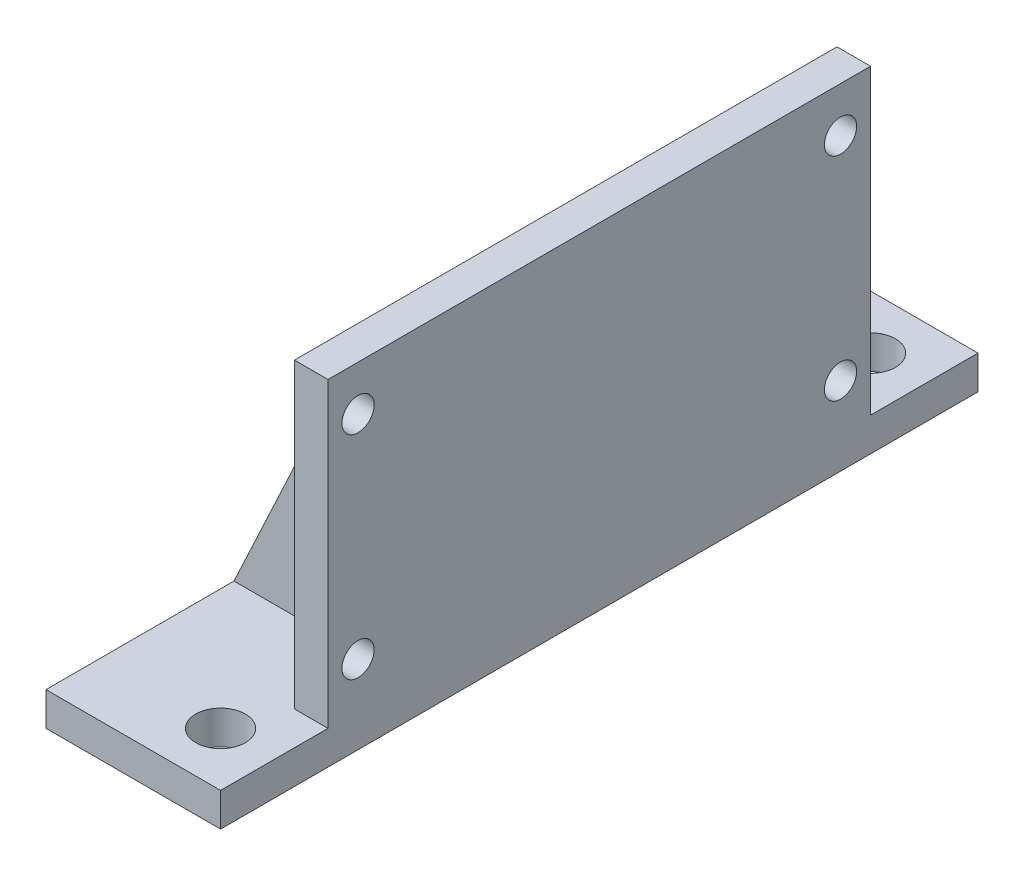
SolidWorks part; units mm, degrees
ref_plane "Front Plane" through (0, 0, 0) normal (0, 0, 1) x (1, 0, 0)
ref_plane "Top Plane" through (0, 0, 0) normal (0, 1, 0) x (1, 0, 0)
ref_plane "Right Plane" through (0, 0, 0) normal (1, 0, 0) x (0, 0, -1)
sketch "Sketch1" plane through (0, 0, 0) normal (0, 1, 0) x (1, 0, 0)
  line L0 (0, 0) -> (0, 61.4723)
  line L2 (0, 0) -> (-5.08, 0)
  line L3 (0, 0) -> (0, 5.08)
  line L4 (0, 5.08) -> (-5.08, 5.08)
  line L5 (-5.08, 0) -> (-5.08, 5.08)
  line L6 (-5.08, 5.08) -> (5.08, 5.08)
  line L7 (-5.08, 5.08) -> (-5.08, -5.08)
  line L8 (-5.08, -5.08) -> (5.08, -5.08)
  line L9 (5.08, 5.08) -> (5.08, -5.08)
  line L10 (0, 61.4723) -> (5.08, 61.4723)
  line L11 (0, 61.4723) -> (0, 56.3923)
  line L12 (0, 56.3923) -> (5.08, 56.3923)
  line L13 (5.08, 61.4723) -> (5.08, 56.3923)
  line L14 (5.08, 56.3923) -> (-5.08, 56.3923)
  line L15 (5.08, 56.3923) -> (5.08, 66.5523)
  line L16 (5.08, 66.5523) -> (-5.08, 66.5523)
  line L17 (-5.08, 56.3923) -> (-5.08, 66.5523)
  line L18 (-5.08, 56.3923) -> (5.08, 56.3923)
  line L19 (-5.08, 56.3923) -> (-5.08, 5.08)
  line L20 (-5.08, 5.08) -> (5.08, 5.08)
  line L21 (5.08, 56.3923) -> (5.08, 5.08)
  line L22 (-5.08, 66.5523) -> (-11.43, 66.5523)
  line L23 (-5.08, 66.5523) -> (-5.08, -5.08)
  line L24 (-5.08, -5.08) -> (-11.43, -5.08)
  line L25 (-11.43, 66.5523) -> (-11.43, -5.08)
  circle A1 centre (0, 61.4723) radius 2.3495
  circle A2 centre (0, 0) radius 2.3495
  dimension "D2" = 4.699
  dimension "D3" = 4.699
  dimension "D1" = 61.4723
  dimension "D4" = 5.08
  dimension "D5" = 10.16
  dimension "D6" = 5.08
  dimension "D7" = 10.16
  dimension "D8" = 6.35
extrude "Boss-Extrude1" add sketch "Sketch1" along normal blind 3.175 contours A1 L10 L15 L16 L17 L14 L0 | A1 L0 L12 L13 L10 | L14 L19 L4 L0 | L21 L12 L0 L6 | A2 L3 L4 L5 L2 | A2 L2 L7 L8 L9 L6 L3 | L22 L25 L24 L7 L5 L19 L17
sketch "Sketch2" plane through (5.08, 0, 0) normal (1, 0, 0) x (0, 0, -1)
  line L1 (5.08, 3.175) -> (56.3923, 3.175)
  line L2 (5.08, 3.175) -> (5.08, 31.75)
  line L3 (5.08, 31.75) -> (56.3923, 31.75)
  line L4 (56.3923, 3.175) -> (56.3923, 31.75)
  line L5 (66.5523, 3.175) -> (66.5523, 0)
  line L6 (-5.08, 3.175) -> (66.5523, 3.175) construction
  line L7 (-5.08, 3.175) -> (66.5523, 3.175)
  line L8 (7.9214, 27.4955) -> (7.9214, 7.4295) construction
  line L9 (7.9214, 7.4295) -> (24.6813, 7.4295) construction
  line L10 (53.5509, 27.4955) -> (53.5509, 7.4295) construction
  line L11 (7.9214, 17.4625) -> (53.5509, 17.4625) construction
  line L12 (5.08, 31.75) -> (56.3923, 3.175) construction
  line L13 (30.7361, 17.4625) -> (44.0356, 17.4625) construction
  circle A0 centre (7.9214, 27.4955) radius 1.524
  circle A1 centre (53.5509, 27.4955) radius 1.524
  circle A2 centre (53.5509, 7.4295) radius 1.524
  circle A3 centre (7.9214, 7.4295) radius 1.524
  line M5 (66.5523, 3.175) -> (-5.08, 3.175)
  dimension "D2" = 3.048
  dimension "D3" = 3.048
  dimension "D4" = 3.048
  dimension "D5" = 3.048
  dimension "D1" = 28.575
  dimension "D6" = 10.16
  dimension "D7" = 10.16
  dimension "D8" = 20.066
  dimension "D9" = 45.6295
  dimension "D10" = 20.066
extrude "Boss-Extrude2" add sketch "Sketch2" against normal blind 3.175 contours L4 L3 L2 A3 A2 A1 A0 M5
ref_plane "Plane1" through (0, 0, -30.7361) normal (0, 0, 1) x (1, 0, 0)
ref_plane "Plane2" through (0, 0, -48.7723) normal (0, 0, -1) x (-1, 0, 0)
sketch "Sketch3" plane through (0, 0, -48.7723) normal (0, 0, -1) x (-1, 0, 0)
  line L0 (-1.905, 3.175) -> (-1.905, 31.75) construction
  line L1 (-1.905, 3.175) -> (-1.905, 31.75)
  line L2 (-5.08, 3.175) -> (11.43, 3.175) construction
  line L3 (-5.08, 3.175) -> (11.43, 3.175)
  line L4 (-1.905, 31.75) -> (11.43, 3.175)
extrude "Boss-Extrude3" add sketch "Sketch3" against normal blind 2.54 contours L4 L1 L3
mirror "Mirror1" about plane through (0, 0, -30.7361) normal (0, 0, 1) of "Boss-Extrude3"
